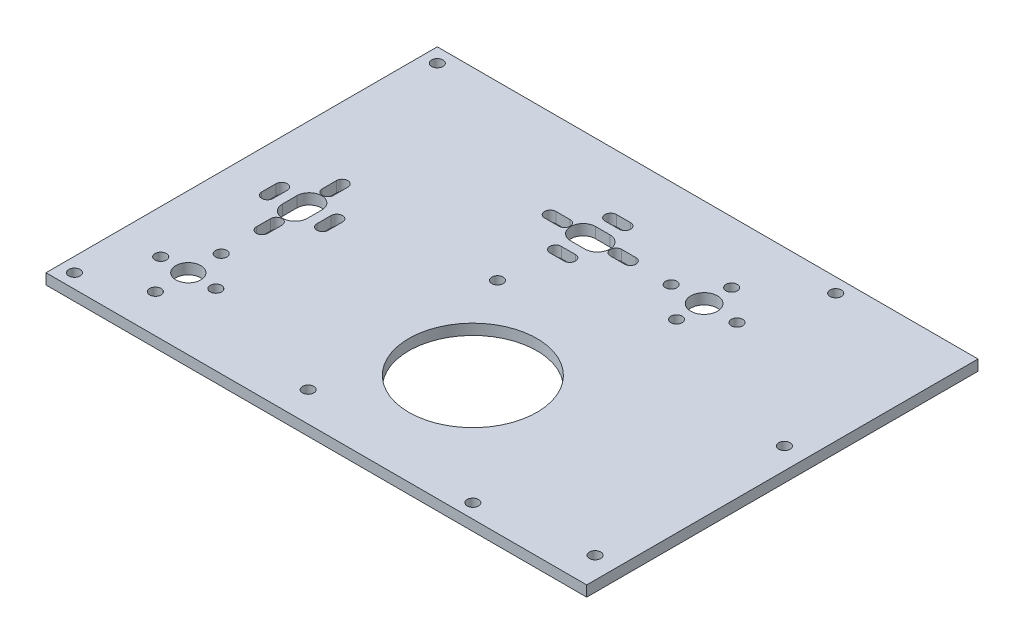
SolidWorks part; units mm, degrees
ref_plane "前视基准面" through (0, 0, 0) normal (0, 0, 1) x (1, 0, 0)
ref_plane "上视基准面" through (0, 0, 0) normal (0, 1, 0) x (1, 0, 0)
ref_plane "右视基准面" through (0, 0, 0) normal (1, 0, 0) x (0, 0, -1)
sketch "Sketch1" plane through (0, 0, 0) normal (0, 1, 0) x (1, 0, 0)
  line L1 (-60, 55) -> (60, 55)
  line L2 (-60, 55) -> (-60, -55)
  line L3 (-60, -55) -> (60, -55)
  line L4 (60, 55) -> (60, -55)
  line L5 (0, -55) -> (0, 55) construction
  line L6 (-60, 0) -> (60, 0) construction
  point P0 (0, 0)
  dimension "D1" = 120
  dimension "D2" = 110
extrude "Boss-Extrude1" add sketch "Sketch1" along normal blind 3
sketch "Sketch2" plane through (0, 3, 0) normal (0, 1, 0) x (1, 0, 0)
  line L0 (60, -55) -> (60, 55) construction
  line L1 (60, 55) -> (-60, 55) construction
  line L2 (-60, -55) -> (60, -55) construction
  line L3 (-60, 55) -> (-60, -55) construction
  line L4 (10, 30) -> (19.25, 30) construction
  line L5 (-40, -5) -> (-40, -14.25) construction
  line L6 (40, 30) -> (49.25, 30) construction
  line L8 (-40, -35) -> (-40, -44.25) construction
  circle A0 centre (40, 30) radius 14.25 construction
  circle A1 centre (10, 30) radius 14.25 construction
  circle A2 centre (-40, -5) radius 14.25 construction
  circle A3 centre (-40, -35) radius 14.25 construction
  circle A5 centre (19.25, 30) radius 1.6
  circle A6 centre (49.25, 30) radius 1.6
  circle A7 centre (-40, -14.25) radius 1.6
  circle A8 centre (-40, -44.25) radius 1.6
  circle A9 centre (0.75, 30) radius 1.6
  circle A12 centre (30.75, 30) radius 1.6
  circle A15 centre (-40, -25.75) radius 1.6
  circle A19 centre (-40, 4.25) radius 1.6
  circle A24 centre (-47.75, -5) radius 1.6
  circle A25 centre (-40, 34.25) radius 1.6 [skipped]
  circle A26 centre (-32.25, -5) radius 1.6
  circle A27 centre (-47.75, -35) radius 1.6
  circle A28 centre (-32.25, -35) radius 1.6
  circle A29 centre (10, 22.25) radius 1.6
  circle A30 centre (10, 37.75) radius 1.6
  circle A31 centre (40, 22.25) radius 1.6
  circle A32 centre (40, 37.75) radius 1.6
  point P33 (10, 30)
  point P40 (40, 30)
  point P47 (-40, -35)
  point P51 (0, 0)
  point P52 (0, 0)
  point P53 (0, 0)
  point P54 (0, 0)
  point P55 (0, 0)
  point P56 (0, 0)
  point P57 (0, 0)
  point P58 (0, 0)
  point P59 (0, 0)
  point P60 (-40, -5)
  point P61 (0, 0)
  dimension "D1" = 28.5
  dimension "D8" = 3.2
  dimension "D11" = 3.2
  dimension "D2" = 20
  dimension "D3" = 25
  dimension "D4" = 20
  dimension "D5" = 20
  dimension "D6" = 30
  dimension "D7" = 30
  dimension "D9" = 9.25
  dimension "D10" = 9.25
  dimension "D12" = 9.25
  dimension "D17" = 15.5
  dimension "D18" = 7.75
  dimension "D19" = 15.5
  dimension "D20" = 7.75
  dimension "D13" = 2
  dimension "D14" = 2
  dimension "D15" = 2
  dimension "D16" = 2
extrude "Cut-Extrude1" cut sketch "Sketch2" against normal blind 4
sketch "Sketch3" plane through (0, 3, 0) normal (0, 1, 0) x (1, 0, 0)
  line L0 (-40, -14.25) -> (-40, -25.75) construction
  line L2 (19.25, 30) -> (30.75, 30) construction
  line L4 (-40, -20) -> (25, -20) construction
  line L5 (25, -20) -> (25, 30) construction
  circle A0 centre (25, -20) radius 18
  circle A1 centre (25, -8.75) radius 1.6 construction
  circle A2 centre (36.25, -20) radius 1.6 construction
  circle A3 centre (25, -31.25) radius 1.6 construction
  circle A4 centre (13.75, -20) radius 1.6 construction
  point P14 (-40, -27)
  point P15 (32, 30)
  point P23 (25, -20)
  dimension "D1" = 36
  dimension "D2" = 11.25
  dimension "D3" = 3.2
  dimension "D4" = 4
extrude "Cut-Extrude2" cut sketch "Sketch3" against normal blind 10
sketch "Sketch4" plane through (0, 3, 0) normal (0, 1, 0) x (1, 0, 0)
  line L0 (-40, -14.25) -> (-40, -10.25) construction
  line L3 (-41.6, -14.25) -> (-41.6, -10.25)
  line L6 (-38.4, -14.25) -> (-38.4, -10.25)
  line L9 (-40, 4.25) -> (-40, 8.25) construction
  line L12 (-41.6, 4.25) -> (-41.6, 8.25)
  line L15 (-38.4, 4.25) -> (-38.4, 8.25)
  line L18 (19.25, 30) -> (15.25, 30) construction
  line L21 (19.25, 28.4) -> (15.25, 28.4)
  line L24 (19.25, 31.6) -> (15.25, 31.6)
  line L25 (0.75, 30) -> (-3.25, 30) construction
  line L26 (0.75, 28.4) -> (-3.25, 28.4)
  line L27 (0.75, 31.6) -> (-3.25, 31.6)
  line L28 (-32.25, -5) -> (-32.25, -1) construction
  line L29 (-33.85, -5) -> (-33.85, -1)
  line L30 (-30.65, -5) -> (-30.65, -1)
  line L31 (-47.75, -5) -> (-47.75, -1) construction
  line L32 (-49.35, -5) -> (-49.35, -1)
  line L33 (-46.15, -5) -> (-46.15, -1)
  line L34 (10, 22.25) -> (6, 22.25) construction
  line L35 (10, 20.65) -> (6, 20.65)
  line L36 (10, 23.85) -> (6, 23.85)
  line L37 (10, 37.75) -> (6, 37.75) construction
  line L38 (10, 36.15) -> (6, 36.15)
  line L39 (10, 39.35) -> (6, 39.35)
  arc A17 (-41.6, -14.25) -> (-38.4, -14.25) centre (-40, -14.25) ccw
  arc A18 (-38.4, -10.25) -> (-41.6, -10.25) centre (-40, -10.25) ccw
  arc A19 (-41.6, 4.25) -> (-38.4, 4.25) centre (-40, 4.25) ccw
  arc A20 (-38.4, 8.25) -> (-41.6, 8.25) centre (-40, 8.25) ccw
  arc A21 (19.25, 28.4) -> (19.25, 31.6) centre (19.25, 30) ccw
  arc A22 (15.25, 31.6) -> (15.25, 28.4) centre (15.25, 30) ccw
  arc A23 (0.75, 28.4) -> (0.75, 31.6) centre (0.75, 30) ccw
  arc A24 (-3.25, 31.6) -> (-3.25, 28.4) centre (-3.25, 30) ccw
  circle A25 centre (-40, -14.25) radius 1.6 construction
  arc A26 (-33.85, -5) -> (-30.65, -5) centre (-32.25, -5) ccw
  arc A27 (-30.65, -1) -> (-33.85, -1) centre (-32.25, -1) ccw
  arc A28 (-49.35, -5) -> (-46.15, -5) centre (-47.75, -5) ccw
  arc A29 (-46.15, -1) -> (-49.35, -1) centre (-47.75, -1) ccw
  arc A30 (10, 20.65) -> (10, 23.85) centre (10, 22.25) ccw
  arc A31 (6, 23.85) -> (6, 20.65) centre (6, 22.25) ccw
  arc A32 (10, 36.15) -> (10, 39.35) centre (10, 37.75) ccw
  arc A33 (6, 39.35) -> (6, 36.15) centre (6, 37.75) ccw
  point P3 (-40, -12.25)
  point P8 (-40, 6.25)
  point P16 (17.25, 30)
  point P24 (-1.25, 30)
  point P37 (-32.25, -3)
  point P42 (-47.75, -3)
  point P50 (8, 22.25)
  point P58 (8, 37.75)
  dimension "D1" = 4
extrude "Cut-Extrude3" cut sketch "Sketch4" against normal blind 10
sketch "Sketch5" plane through (0, 3, 0) normal (0, 1, 0) x (1, 0, 0)
  line L0 (-60, -55) -> (60, -55) construction
  line L1 (-56, -51) -> (56, -51) construction
  line L2 (-56, -51) -> (-56, 51) construction
  line L3 (-56, 51) -> (56, 51) construction
  line L4 (56, -51) -> (56, 51) construction
  line L5 (0, 51) -> (0, -51) construction
  line L6 (-56, 0) -> (56, 0) construction
  line L7 (-60, 55) -> (-60, -55) construction
  circle A0 centre (-56, 51) radius 1.6
  circle A1 centre (56, 51) radius 1.6
  circle A2 centre (56, -51) radius 1.6
  circle A3 centre (-56, -51) radius 1.6
  point P0 (0, 0)
  dimension "D1" = 3.2
  dimension "D2" = 4
  dimension "D3" = 4
extrude "Cut-Extrude5" cut sketch "Sketch5" against normal blind 10
sketch "Sketch6" plane through (0, 3, 0) normal (0, 1, 0) x (1, 0, 0)
  line L0 (30.75, 30) -> (49.25, 30) construction
  line L1 (-40, -5) -> (-40, -1) construction
  line L2 (-40, -25.75) -> (-40, -44.25) construction
  line L3 (-43.5, -5) -> (-43.5, -1)
  line L4 (-40, -14.25) -> (-40, 4.25) construction
  line L5 (-36.5, -5) -> (-36.5, -1)
  line L6 (0.75, 30) -> (19.25, 30) construction
  line L9 (10, 30) -> (6, 30) construction
  line L10 (10, 26.5) -> (6, 26.5)
  line L11 (10, 33.5) -> (6, 33.5)
  arc A0 (-43.5, -5) -> (-36.5, -5) centre (-40, -5) ccw
  arc A1 (-36.5, -1) -> (-43.5, -1) centre (-40, -1) ccw
  circle A3 centre (-40, -35) radius 3.5
  arc A4 (10, 26.5) -> (10, 33.5) centre (10, 30) ccw
  arc A5 (6, 33.5) -> (6, 26.5) centre (6, 30) ccw
  circle A6 centre (40, 30) radius 3.75
  point P18 (-40, -3)
  point P27 (8, 30)
  point P34 (0, 0)
  point P35 (48, 30)
  point P37 (40, 30)
  point P38 (0, 0)
  point P39 (2, 30)
  point P41 (0, 0)
  point P42 (-40, -27)
  point P44 (0, 0)
  point P45 (-40, 3)
  dimension "D1" = 3.5
  dimension "D3" = 7
  dimension "D4" = 7.5
  dimension "D6" = 3.5
  dimension "D2" = 4
  dimension "D5" = 4
extrude "Cut-Extrude6" cut sketch "Sketch6" against normal blind 10
sketch "Sketch9" plane through (60, 0, 0) normal (1, 0, 0) x (0, 0, -1)
  line L4 (-55, 0) -> (55, 0)
  line L5 (55, 0) -> (55, 3)
  line L6 (55, 3) -> (-55, 3)
  line L7 (-55, 3) -> (-55, 0)
  line L8 (-55, 0) -> (55, 0)
  line L9 (55, 0) -> (55, 3)
  line L10 (55, 3) -> (-55, 3)
  line L11 (-55, 3) -> (-55, 0)
  dimension "D1" = 0
extrude "Boss-Extrude2" add sketch "Sketch9" along normal blind 32
sketch "Sketch8" plane through (0, 0, 0) normal (0, -1, 0) x (1, 0, 0)
  line L1 (85.96, 46.608) -> (5.315, 46.608) construction
  line L2 (85.96, 46.608) -> (85.96, -6.608) construction
  line L3 (85.96, -6.608) -> (5.315, -6.608) construction
  line L4 (5.315, 46.608) -> (5.315, -6.608) construction
  line L5 (45.6375, -6.608) -> (45.6375, 46.608) construction
  line L6 (85.96, 20) -> (5.315, 20) construction
  circle A0 centre (25, 20) radius 9.4474 construction
  circle A1 centre (5.315, -6.608) radius 1.6
  circle A2 centre (5.315, 46.608) radius 1.6
  circle A3 centre (85.96, 46.608) radius 1.6
  circle A4 centre (85.96, -6.608) radius 1.6
  point P3 (45.6375, 20)
  dimension "D1" = 19.685
  dimension "D4" = 3.2
  dimension "D5" = 26.608
  dimension "D2" = 53.216
  dimension "D3" = 80.645
extrude "Cut-Extrude8" cut sketch "Sketch8" against normal blind 10
sketch "Sketch11" plane through (0, 0, 0) normal (0, -1, 0) x (1, 0, 0)
  line L8 (-49.35, 0) -> (-49.35, 5) construction
  line L9 (-46.65, 5) -> (-46.65, 0) construction
  line L10 (-33.35, 0) -> (-33.35, 5) construction
  line L11 (-30.65, 5) -> (-30.65, 0) construction
  line L12 (-49.35, 0) -> (-49.35, 5)
  line L13 (-46.65, 5) -> (-46.65, 0)
  line L14 (-33.35, 0) -> (-33.35, 5)
  line L15 (-30.65, 5) -> (-30.65, 0)
  line L17 (-50.85, 0) -> (-50.85, 5)
  line L18 (-45.15, 5) -> (-45.15, 0)
  line L19 (-34.85, 0) -> (-34.85, 5)
  line L20 (-29.15, 5) -> (-29.15, 0)
  line L21 (10, -25) -> (5, -25)
  line L22 (0.8918, -27.15) -> (-3, -27.15)
  line L23 (10, -26.5) -> (5, -26.5)
  line L24 (18, -28.65) -> (13.2292, -28.65)
  line L25 (13.2292, -31.35) -> (18, -31.35)
  line L26 (5, -33.5) -> (10, -33.5)
  line L27 (-3, -31.35) -> (1.7708, -31.35)
  line L28 (1.7708, -28.65) -> (-3, -28.65)
  line L29 (10, -26.5) -> (5, -26.5)
  line L30 (18, -28.65) -> (13.2292, -28.65)
  line L31 (13.2292, -31.35) -> (18, -31.35)
  line L32 (5, -33.5) -> (10, -33.5)
  line L33 (-3, -31.35) -> (1.7708, -31.35)
  line L34 (1.7708, -28.65) -> (-3, -28.65)
  line L35 (-3, -32.85) -> (0.8918, -32.85)
  line L36 (5, -35) -> (10, -35)
  line L37 (14.1082, -32.85) -> (18, -32.85)
  line L38 (18, -27.15) -> (14.1082, -27.15)
  circle A4 centre (-40, 27) radius 1.35 construction
  circle A5 centre (-40, 43) radius 1.35 construction
  circle A6 centre (-32, 35) radius 1.35 construction
  circle A7 centre (-48, 35) radius 1.35 construction
  circle A8 centre (-40, 27) radius 1.35
  circle A9 centre (-40, 43) radius 1.35
  circle A10 centre (-32, 35) radius 1.35
  circle A11 centre (-48, 35) radius 1.35
  circle A16 centre (48, -30) radius 1.35 construction
  circle A17 centre (40, -22) radius 1.35 construction
  circle A18 centre (32, -30) radius 1.35 construction
  circle A19 centre (40, -38) radius 1.35 construction
  circle A24 centre (48, -30) radius 1.35
  circle A25 centre (40, -22) radius 1.35
  circle A26 centre (32, -30) radius 1.35
  circle A27 centre (40, -38) radius 1.35
  arc A28 (-49.35, 0) -> (-46.65, 0) centre (-48, 0) ccw construction
  arc A29 (-46.65, 5) -> (-49.35, 5) centre (-48, 5) ccw construction
  arc A30 (-33.35, 0) -> (-30.65, 0) centre (-32, 0) ccw construction
  arc A31 (-30.65, 5) -> (-33.35, 5) centre (-32, 5) ccw construction
  arc A32 (-49.35, 0) -> (-46.65, 0) centre (-48, 0) ccw
  arc A33 (-46.65, 5) -> (-49.35, 5) centre (-48, 5) ccw
  arc A34 (-33.35, 0) -> (-30.65, 0) centre (-32, 0) ccw
  arc A35 (-30.65, 5) -> (-33.35, 5) centre (-32, 5) ccw
  arc A36 (-45.15, 5) -> (-50.85, 5) centre (-48, 5) ccw
  arc A37 (-50.85, 0) -> (-45.15, 0) centre (-48, 0) ccw
  arc A38 (-29.15, 5) -> (-34.85, 5) centre (-32, 5) ccw
  arc A39 (-34.85, 0) -> (-29.15, 0) centre (-32, 0) ccw
  arc A40 (5, -25) -> (0.8918, -27.15) centre (5, -30) ccw
  arc A41 (-3, -27.15) -> (-3, -32.85) centre (-3, -30) ccw
  arc A42 (13.2292, -28.65) -> (10, -26.5) centre (10, -30) ccw
  arc A43 (18, -31.35) -> (18, -28.65) centre (18, -30) ccw
  arc A44 (10, -33.5) -> (13.2292, -31.35) centre (10, -30) ccw
  arc A45 (1.7708, -31.35) -> (5, -33.5) centre (5, -30) ccw
  arc A46 (-3, -28.65) -> (-3, -31.35) centre (-3, -30) ccw
  arc A47 (5, -26.5) -> (1.7708, -28.65) centre (5, -30) ccw
  arc A48 (13.2292, -28.65) -> (10, -26.5) centre (10, -30) ccw
  arc A49 (18, -31.35) -> (18, -28.65) centre (18, -30) ccw
  arc A50 (10, -33.5) -> (13.2292, -31.35) centre (10, -30) ccw
  arc A51 (1.7708, -31.35) -> (5, -33.5) centre (5, -30) ccw
  arc A52 (-3, -28.65) -> (-3, -31.35) centre (-3, -30) ccw
  arc A53 (5, -26.5) -> (1.7708, -28.65) centre (5, -30) ccw
  arc A54 (0.8918, -32.85) -> (5, -35) centre (5, -30) ccw
  arc A55 (10, -35) -> (14.1082, -32.85) centre (10, -30) ccw
  arc A56 (18, -32.85) -> (18, -27.15) centre (18, -30) ccw
  arc A57 (14.1082, -27.15) -> (10, -25) centre (10, -30) ccw
  circle A58 centre (-40, 27) radius 2.85
  circle A59 centre (-40, 43) radius 2.85
  circle A60 centre (-32, 35) radius 2.85
  circle A61 centre (-48, 35) radius 2.85
  circle A62 centre (48, -30) radius 2.85
  circle A63 centre (40, -22) radius 2.85
  circle A64 centre (32, -30) radius 2.85
  circle A65 centre (40, -38) radius 2.85
  dimension "D1" = 0
  dimension "D2" = 1.5
extrude "Boss-Extrude3" [suppressed] add sketch "Sketch11" along normal blind 5
equation "\"D4@Sketch2\"=\"D5@Sketch2\""
equation "\"D2@Sketch2\"=\"D5@Sketch2\""
equation "\"D3@Sketch5\"=\"D2@Sketch5\""
equation "\"D9@Sketch2\"=\"D10@Sketch2\""
